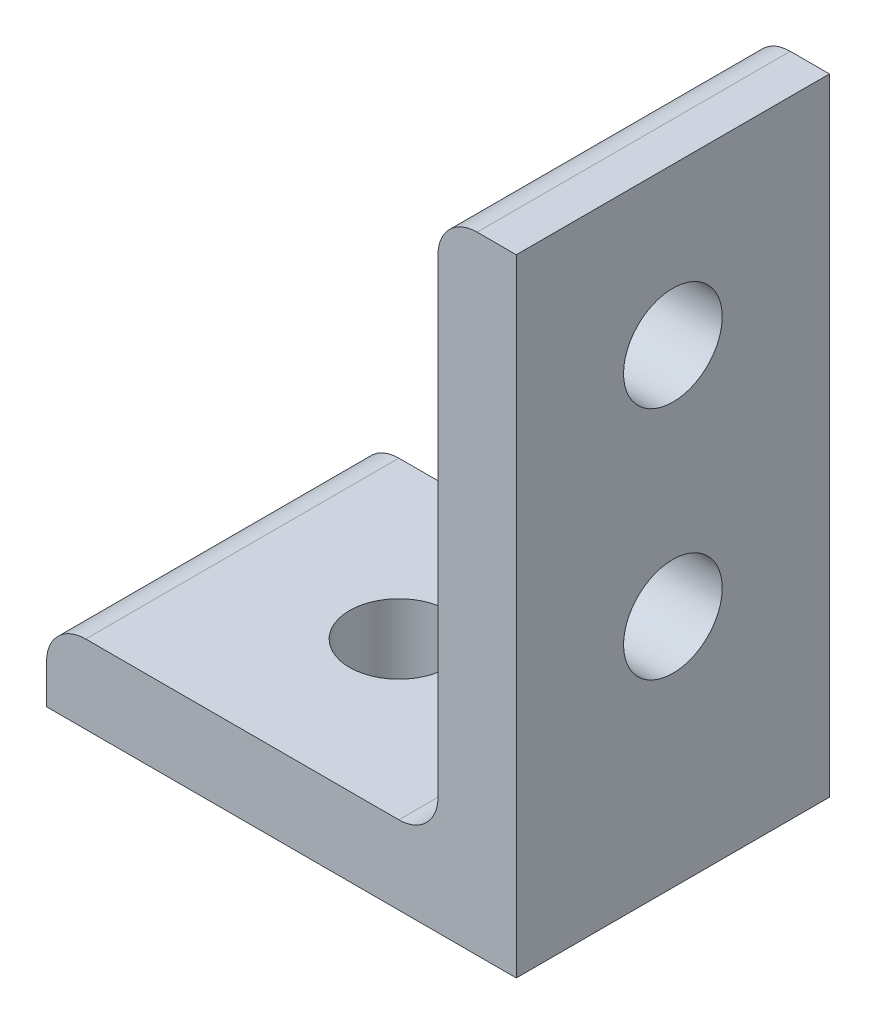
SolidWorks part; units mm, degrees
ref_plane "Front Plane" through (0, 0, 0) normal (0, 0, 1) x (1, 0, 0)
ref_plane "Top Plane" through (0, 0, 0) normal (0, 1, 0) x (1, 0, 0)
ref_plane "Right Plane" through (0, 0, 0) normal (1, 0, 0) x (0, 0, -1)
sketch "Sketch2" plane through (0, 0, 0) normal (0, 0, 1) x (1, 0, 0)
  line L0 (-19.05, 0) -> (19.05, 0)
  line L1 (19.05, 0) -> (19.05, 50.8)
  line L2 (19.05, 50.8) -> (12.7, 50.8) construction
  line L3 (12.7, 47.625) -> (12.7, 9.525)
  line L4 (9.525, 6.35) -> (-15.875, 6.35)
  line L5 (-19.05, 0) -> (-19.05, 6.35) construction
  line L6 (15.875, 50.8) -> (19.05, 50.8)
  line L7 (-19.05, 3.175) -> (-19.05, 0)
  arc A0 (12.7, 47.625) -> (15.875, 50.8) centre (15.875, 47.625) cw
  arc A1 (-19.05, 3.175) -> (-15.875, 6.35) centre (-15.875, 3.175) cw
  arc A2 (12.7, 9.525) -> (9.525, 6.35) centre (9.525, 9.525) cw
  dimension "Vert" = 50.8
  dimension "Horz" = 38.1
  dimension "Thickness" = 6.35
extrude "Boss-Extrude1" add sketch "Sketch2" along normal mid plane 25.4
ref_plane "Contact Plane 1" through (0, 6.35, 0) normal (0, 1, 0) x (1, 0, 0)
ref_plane "Contact Plane 2" through (12.7, 0, 0) normal (-1, 0, 0) x (0, 0, 1)
sketch "Sketch3" plane through (0, 6.35, 0) normal (0, 1, 0) x (1, 0, 0)
  line L0 (-3.175, 12.7) -> (-3.175, -12.7) construction
  line L1 (9.525, 12.7) -> (-15.875, 12.7) construction
  line L2 (9.525, -12.7) -> (-15.875, -12.7) construction
  line L3 (-15.875, 0) -> (9.525, 0) construction
  line L4 (-15.875, -12.7) -> (-15.875, 12.7) construction
  line L5 (9.525, -12.7) -> (9.525, 12.7) construction
  circle A0 centre (-3.175, 0) radius 4
  circle A1 centre (-3.175, 0) radius 7 construction
  dimension "D1" = 8
  dimension "D2" = 14
extrude "Cut-Extrude1" cut sketch "Sketch3" against normal through all
sketch "Sketch4" plane through (12.7, 0, 0) normal (-1, 0, 0) x (0, 0, 1)
  line L0 (0, 47.625) -> (0, 9.525) construction
  line L1 (12.7, 47.625) -> (-12.7, 47.625) construction
  line L2 (12.7, 9.525) -> (-12.7, 9.525) construction
  line L3 (-12.7, 28.575) -> (12.7, 28.575) construction
  line L4 (-12.7, 47.625) -> (-12.7, 9.525) construction
  line L5 (12.7, 47.625) -> (12.7, 9.525) construction
  line L6 (12.7, 28.575) -> (12.7, 47.625) construction
  line L7 (12.7, 38.1) -> (-12.7, 38.1) construction
  circle A0 centre (0, 38.1) radius 4
  circle A1 centre (0, 19.05) radius 4
  circle A2 centre (0, 38.1) radius 7 construction
  dimension "D1" = 8
  dimension "D2" = 14
extrude "Cut-Extrude2" cut sketch "Sketch4" against normal through all
